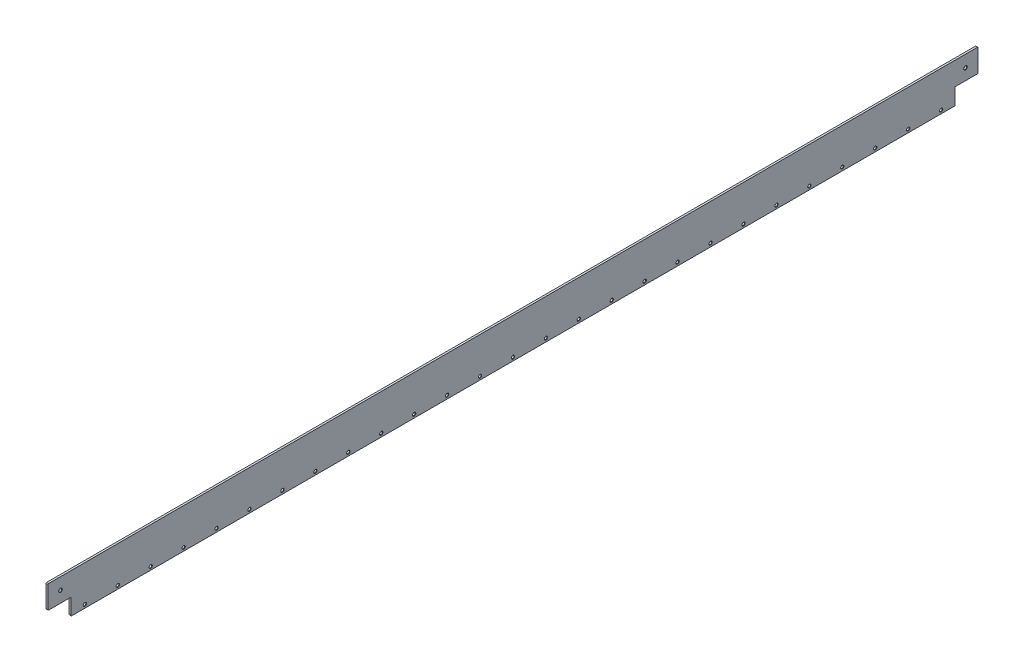
SolidWorks part; units mm, degrees
material "Plain Carbon Steel"
ref_plane "Front Plane" through (0, 0, 0) normal (0, 0, 1) x (1, 0, 0)
ref_plane "Top Plane" through (0, 0, 0) normal (0, 1, 0) x (1, 0, 0)
ref_plane "Right Plane" through (0, 0, 0) normal (1, 0, 0) x (0, 0, -1)
sketch "Sketch1" plane through (0, 0, 0) normal (1, 0, 0) x (0, 0, -1)
  line L0 (-706, 30) -> (-706, -5)
  line L1 (-706, -30) -> (706, -30) construction
  line L2 (-706, -30) -> (-706, 30) construction
  line L3 (-706, 30) -> (706, 30)
  line L4 (706, -30) -> (706, 30) construction
  line L5 (-706, -30) -> (706, 30) construction
  line L6 (-706, 30) -> (706, -30) construction
  line L7 (-706, -5) -> (-671, -30) construction
  line L8 (-671, -30) -> (671, -30)
  line L9 (671, -30) -> (706, -5) construction
  line L10 (706, -5) -> (706, 30)
  line L11 (-706, -5) -> (-671, -5)
  line L12 (-671, -5) -> (-671, -30)
  line L13 (706, -5) -> (671, -5)
  line L14 (671, -5) -> (671, -30)
  point P0 (0, 0)
  point P11 (0, -30)
  dimension "D1" = 35
  dimension "D2" = 1412
  dimension "D3" = 60
  dimension "D4" = 35
extrude "Boss-Extrude1" add sketch "Sketch1" along normal blind 3
sketch "Sketch2" plane through (3, 0, 0) normal (1, 0, 0) x (0, 0, -1)
  line L0 (-671, -30) -> (671, -30) construction
  circle A0 centre (0, -25) radius 2
  dimension "D1" = 4
  dimension "D2" = 5
extrude "Cut-Extrude1" cut sketch "Sketch2" against normal blind 3
chamfer "Chamfer1" distance 0.5 angle 45 1 edges at (3, -25, -2)
pattern_linear "LPattern1" count 14 spacing 50 along (0, 0, 1) count 14 spacing 50 along (0, 0, -1) of "Chamfer1", "Cut-Extrude1"
fillet "Fillet1" radius 1 6 edges at (1.5, 30, -706) (1.5, 30, 706) (1.5, -5, -706) (1.5, -30, -671) (1.5, -30, 671) (1.5, -5, 706)
sketch "Sketch3" plane through (3, 0, 0) normal (1, 0, 0) x (0, 0, -1)
  line L5 (706, -4) -> (706, 29) construction
  line L6 (705, 30) -> (-705, 30) construction
  circle A2 centre (687, 12) radius 2.25
  dimension "D1" = 19
  dimension "D3" = 4.5
  dimension "D2" = 18
extrude "Cut-Extrude2" cut sketch "Sketch3" against normal blind 10
chamfer "Chamfer2" distance 0.5 angle 45 1 edges at (3, 12, -689.25)
mirror "Mirror1" about plane through (0, 0, 0) normal (0, 0, 1) of "Cut-Extrude2", "Chamfer2"
